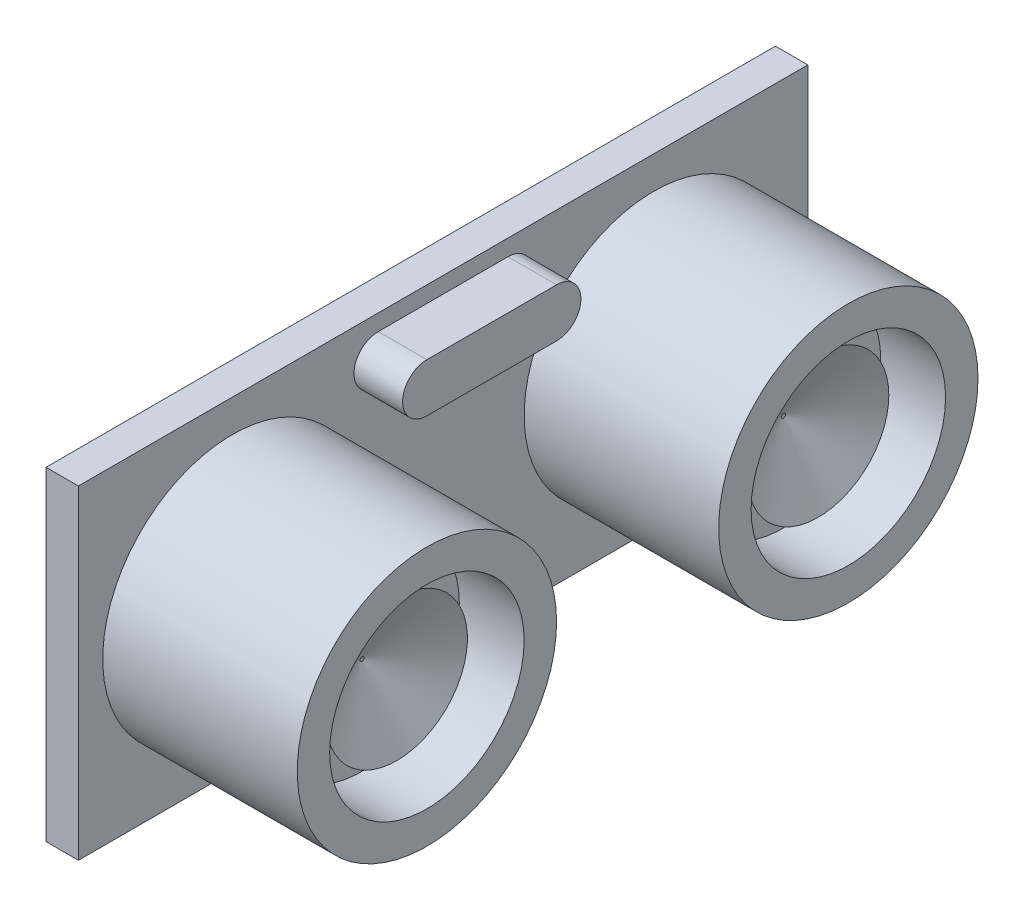
SolidWorks part; units mm, degrees
ref_plane "前视基准面" through (0, 0, 0) normal (0, 0, 1) x (1, 0, 0)
ref_plane "上视基准面" through (0, 0, 0) normal (0, 1, 0) x (1, 0, 0)
ref_plane "右视基准面" through (0, 0, 0) normal (1, 0, 0) x (0, 0, -1)
sketch "草图1" plane through (0, 0, 0) normal (1, 0, 0) x (0, 0, -1)
  line L0 (0, 0) -> (11.9328, 0) construction
  line L1 (-22.5, 10) -> (22.5, 10)
  line L2 (-22.5, 10) -> (-22.5, -10)
  line L3 (-22.5, -10) -> (22.5, -10)
  line L4 (22.5, 10) -> (22.5, -10)
  line L5 (0, 0) -> (0, -22.5359) construction
  dimension "D1" = 20
  dimension "D2" = 45
extrude "凸台-拉伸1" add sketch "草图1" along normal blind 2 contours L1 L4 L3 L2
sketch "草图2" plane through (2, 0, 0) normal (1, 0, 0) x (0, 0, -1)
  line L0 (-4, 7.5) -> (4, 7.5) construction
  line L1 (-4, 9) -> (4, 9)
  line L2 (-4, 6) -> (4, 6)
  line L3 (0, 0) -> (0, -4.0502) construction
  arc A0 (-4, 9) -> (-4, 6) centre (-4, 7.5) ccw
  arc A1 (4, 6) -> (4, 9) centre (4, 7.5) ccw
  point P2 (0, 7.5)
  dimension "D1" = 1.5
  dimension "D2" = 8
  dimension "D3" = 7.5
extrude "凸台-拉伸2" add sketch "草图2" along normal blind 3
sketch "草图3" plane through (2, 0, 0) normal (1, 0, 0) x (0, 0, -1)
  line L0 (0, 0) -> (0, -4.28) construction
  circle A0 centre (-13, 0) radius 8
  circle A1 centre (13, 0) radius 8
  dimension "D1" = 16
  dimension "D2" = 16
  dimension "D3" = 26
extrude "凸台-拉伸3" add sketch "草图3" along normal blind 12
sketch "草图4" plane through (14, 0, 0) normal (1, 0, 0) x (0, 0, -1)
  circle A0 centre (-13, 0) radius 6
  circle A1 centre (13, 0) radius 6
  dimension "D1" = 12
  dimension "D2" = 12
extrude "切除-拉伸1" cut sketch "草图4" against normal blind 4
sketch "草图5" plane through (0, 0, 0) normal (0, 1, 0) x (1, 0, 0)
  line L0 (10, 13) -> (15.0674, 13) construction
  line L2 (10, 13.1237) -> (12.1437, 17.3537)
  line L3 (10, 7) -> (10, 19) construction
  spline S0 degree 2 poles (12.1437, 17.3537) (9.981, 15.8512) (10, 13.1237) knots 0 0 0 1 1 1
revolve "旋转2" add sketch "草图5" angle 360 about L0
mirror "镜向9" about plane through (0, 0, 0) normal (0, 0, 1) of "旋转2"
sketch "草图6" plane through (2, 0, 0) normal (1, 0, 0) x (0, 0, -1)
  text T0 "YB-04"
